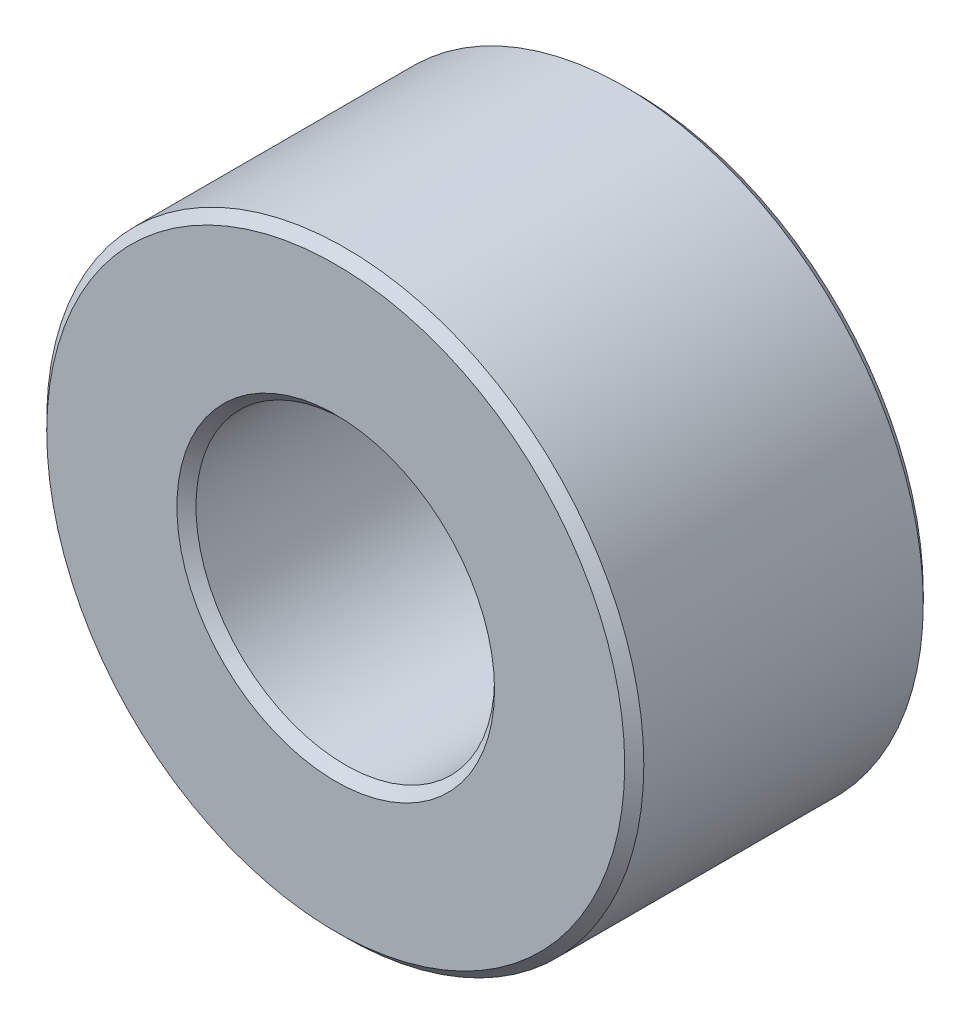
SolidWorks part; units mm, degrees
ref_plane "Front Plane" through (0, 0, 0) normal (0, 0, 1) x (1, 0, 0)
ref_plane "Top Plane" through (0, 0, 0) normal (0, 1, 0) x (1, 0, 0)
ref_plane "Right Plane" through (0, 0, 0) normal (1, 0, 0) x (0, 0, -1)
sketch "Sketch1" plane through (0, 0, 0) normal (0, 0, 1) x (1, 0, 0)
  circle A0 centre (0, 0) radius 7.9375
  dimension "D1" = 15.875
extrude "Boss-Extrude1" add sketch "Sketch1" along normal blind 7.9375
sketch "Sketch2" plane through (0, 0, 7.9375) normal (0, 0, 1) x (1, 0, 0)
  circle A0 centre (0, 0) radius 3.9688
  dimension "D1" = 7.9375
extrude "Cut-Extrude1" cut sketch "Sketch2" against normal blind 7.9375
chamfer "Chamfer1" distance 0.254 angle 45 4 edges at (7.9375, 0, 0) (3.9688, 0, 0) (7.9375, 0, 7.9375) (3.9688, 0, 7.9375)
